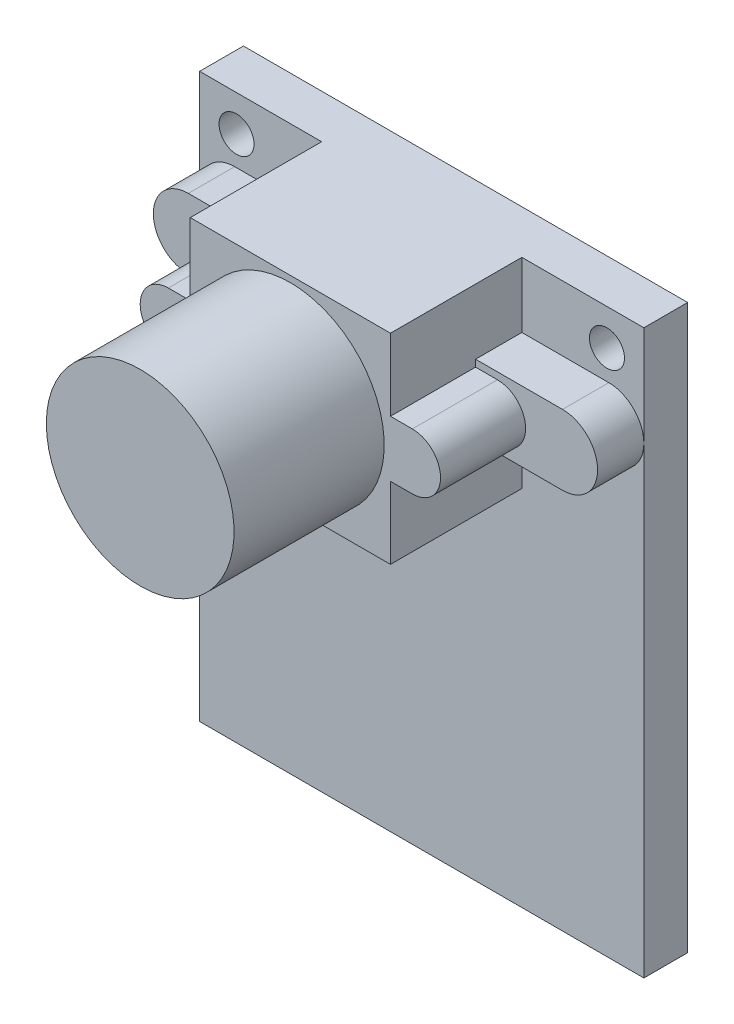
SolidWorks part; units mm, degrees
ref_plane "前视基准面" through (0, 0, 0) normal (0, 0, 1) x (1, 0, 0)
ref_plane "上视基准面" through (0, 0, 0) normal (0, 1, 0) x (1, 0, 0)
ref_plane "右视基准面" through (0, 0, 0) normal (1, 0, 0) x (0, 0, -1)
sketch "草图4" plane through (0, 0, 0) normal (0, 0, 1) x (1, 0, 0)
  line L1 (-17.75, 22.5) -> (17.75, 22.5)
  line L2 (-17.75, 22.5) -> (-17.75, -22.5)
  line L3 (-17.75, -22.5) -> (17.75, -22.5)
  line L4 (17.75, 22.5) -> (17.75, -22.5)
  line L5 (-17.75, 22.5) -> (17.75, -22.5) construction
  line L6 (-17.75, -22.5) -> (17.75, 22.5) construction
  point P0 (0, 0)
  dimension "D1" = 35.5
  dimension "D2" = 45
extrude "凸台-拉伸2" add sketch "草图4" along normal blind 3.5
sketch "草图5" plane through (0, 0, 3.5) normal (0, 0, 1) x (1, 0, 0)
  line L0 (17.75, 22.5) -> (-17.75, 22.5) construction
  line L1 (-8, 22.5) -> (8, 22.5)
  line L2 (-8, 22.5) -> (-8, 6.5)
  line L3 (-8, 6.5) -> (8, 6.5)
  line L4 (8, 22.5) -> (8, 6.5)
  line L5 (0, 33.6696) -> (0, -33.6696) construction
  line L6 (-23.4637, 14.5) -> (28.5006, 14.5) construction
  line L7 (-9.75, 14.5) -> (9.75, 14.5) construction
  line L8 (-9.75, 16.75) -> (9.75, 16.75)
  line L9 (-9.75, 12.25) -> (9.75, 12.25)
  arc A0 (-9.75, 16.75) -> (-9.75, 12.25) centre (-9.75, 14.5) ccw
  arc A1 (9.75, 12.25) -> (9.75, 16.75) centre (9.75, 14.5) ccw
  point P13 (0, 14.5)
  line M12 (17.75, 22.5) -> (-17.75, 22.5)
  dimension "D3" = 24
  dimension "D1" = 16
  dimension "D2" = 16
  dimension "D4" = 4.5
extrude "凸台-拉伸3" add sketch "草图5" along normal blind 14 from surface at -3.5 contours L8 A0 L9 L2 | L2 L9 L4 L8 | L2 L8 L4 M12 | L9 A1 L8 L4 | L9 L2 L3 L4 starting at face at (0, 0, 0)
sketch "草图6" plane through (0, 0, 3.5) normal (0, 0, 1) x (1, 0, 0)
  line L0 (-14.95, 14.5) -> (14.95, 14.5) construction
  line L1 (-14.95, 17.3) -> (14.95, 17.3)
  line L2 (-9.75, 12.25) -> (9.75, 12.25)
  line L3 (9.75, 16.75) -> (-9.75, 16.75)
  line L4 (8, 22.5) -> (-8, 22.5)
  line L5 (8, 6.5) -> (8, 22.5)
  line L6 (-8, 6.5) -> (8, 6.5)
  line L7 (-8, 22.5) -> (-8, 6.5)
  line L8 (8, 22.5) -> (-8, 22.5)
  line L9 (8, 6.5) -> (8, 22.5)
  line L10 (-8, 6.5) -> (8, 6.5)
  line L11 (-8, 22.5) -> (-8, 6.5)
  line L12 (-9.75, 12.25) -> (9.75, 12.25)
  line L13 (9.75, 16.75) -> (-9.75, 16.75)
  line L14 (-14.95, 11.7) -> (14.95, 11.7)
  line L15 (-17.75, 22.5) -> (-17.75, -22.5) construction
  line L16 (17.75, -22.5) -> (17.75, 22.5) construction
  arc A0 (-14.95, 17.3) -> (-14.95, 11.7) centre (-14.95, 14.5) ccw
  arc A1 (14.95, 11.7) -> (14.95, 17.3) centre (14.95, 14.5) ccw
  arc A2 (9.75, 12.25) -> (9.75, 16.75) centre (9.75, 14.5) ccw
  arc A3 (-9.75, 16.75) -> (-9.75, 12.25) centre (-9.75, 14.5) ccw
  arc A4 (9.75, 12.25) -> (9.75, 16.75) centre (9.75, 14.5) ccw
  arc A5 (-9.75, 16.75) -> (-9.75, 12.25) centre (-9.75, 14.5) ccw
  point P12 (0, 14.5)
  dimension "D3" = 5.6
  dimension "D1" = 0
  dimension "D2" = 0
extrude "凸台-拉伸4" add sketch "草图6" along normal blind 7.2 from surface at -3.5 starting at face at (0, 0, 0)
sketch "草图7" plane through (0, 0, 14) normal (0, 0, 1) x (1, 0, 0)
  line L0 (-17.9604, 14.5) -> (-7.5, 14.5)
  line L1 (0, 26.4162) -> (0, 22)
  line L2 (-9.75, 12.25) -> (9.75, 12.25)
  line L3 (9.75, 16.75) -> (-9.75, 16.75)
  line L4 (8, 22.5) -> (-8, 22.5)
  line L5 (8, 6.5) -> (8, 22.5)
  line L6 (-8, 6.5) -> (8, 6.5)
  line L7 (-8, 22.5) -> (-8, 6.5)
  line L8 (8, 22.5) -> (-8, 22.5)
  line L9 (8, 6.5) -> (8, 22.5)
  line L10 (-8, 6.5) -> (8, 6.5)
  line L11 (-8, 22.5) -> (-8, 6.5)
  line L12 (-9.75, 12.25) -> (-7.1545, 12.25)
  line L13 (9.75, 16.75) -> (7.1545, 16.75)
  line L15 (-7.1545, 16.75) -> (-9.75, 16.75)
  line L16 (7.5, 14.5) -> (20.8353, 14.5)
  line L17 (7.1545, 12.25) -> (9.75, 12.25)
  line L18 (0, 7) -> (0, -5.1187)
  circle A0 centre (0, 14.5) radius 7.5
  arc A2 (9.75, 12.25) -> (9.75, 16.75) centre (9.75, 14.5) ccw
  arc A3 (-9.75, 16.75) -> (-9.75, 12.25) centre (-9.75, 14.5) ccw
  arc A4 (9.75, 12.25) -> (9.75, 16.75) centre (9.75, 14.5) ccw
  arc A5 (-9.75, 16.75) -> (-9.75, 12.25) centre (-9.75, 14.5) ccw
  dimension "D3" = 15
  dimension "D1" = 0
  dimension "D2" = 0
extrude "凸台-拉伸5" add sketch "草图7" along normal blind 26 from surface at -14 contours A0 starting at face at (0, 0, 0)
sketch "草图8" plane through (0, 0, 0) normal (0, 0, -1) x (-1, 0, 0)
  line L0 (0, 26.9022) -> (0, -28.8404) construction
  circle A0 centre (-14.8, 19.6266) radius 1.4
  circle A1 centre (14.8, 19.6266) radius 1.4
  dimension "D1" = 2.8
  dimension "D2" = 29.6
extrude "切除-拉伸1" cut sketch "草图8" against normal up to next
